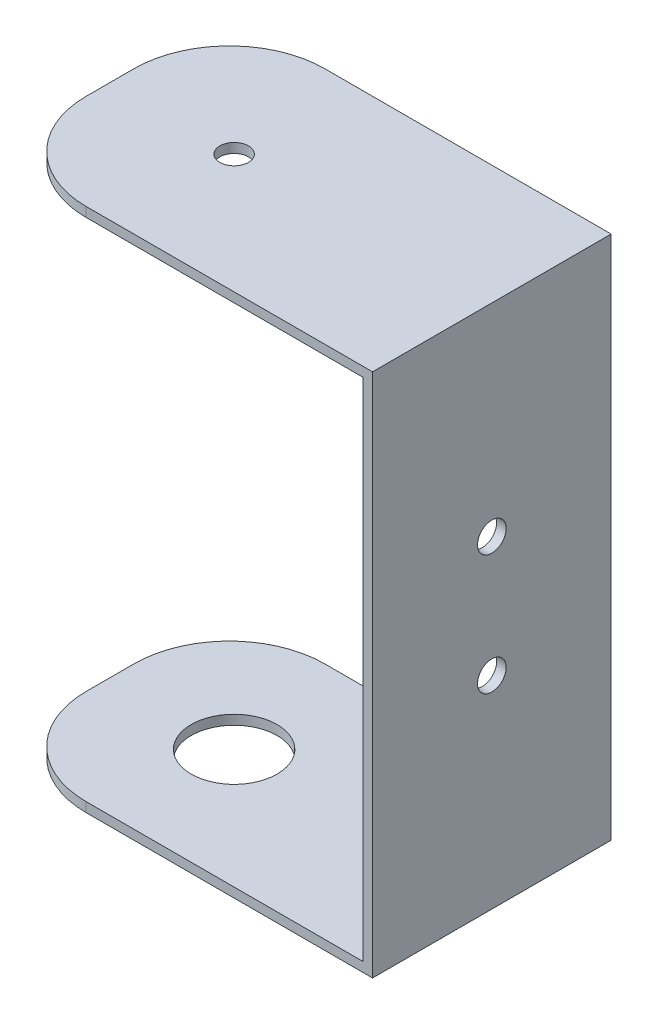
SolidWorks part; units mm, degrees
ref_plane "Alzado" through (0, 0, 0) normal (0, 0, 1) x (1, 0, 0)
ref_plane "Planta" through (0, 0, 0) normal (0, 1, 0) x (1, 0, 0)
ref_plane "Vista lateral" through (0, 0, 0) normal (1, 0, 0) x (0, 0, -1)
sketch "Croquis1" plane through (0, 0, 0) normal (0, 0, 1) x (1, 0, 0)
  line L0 (0, 17.1493) -> (0, -35.8507)
  line L1 (0, -35.8507) -> (-39, -35.8507)
  line L2 (0, 17.1493) -> (-39, 17.1493)
  dimension "D1" = 39
  dimension "D2" = 39
  dimension "D3" = 53
extrude "Extruir-Lámina1" add sketch "Croquis1" along normal blind 25 thin thin type one direction wall 1
sketch "Croquis2" plane through (0, 18.1493, 0) normal (0, 1, 0) x (1, 0, 0)
  circle A0 centre (-26, -12.5) radius 1.5
extrude "Cortar-Extruir1" cut sketch "Croquis2" against normal blind 1
sketch "Croquis5" plane through (0, -36.8507, 0) normal (0, -1, 0) x (1, 0, 0)
  circle A0 centre (-26, 12.5) radius 4.5
extrude "Cortar-Extruir2" cut sketch "Croquis5" against normal blind 1
sketch "Croquis6" plane through (1, 0, 0) normal (1, 0, 0) x (0, 0, -1)
  circle A0 centre (-12.5, -15.6507) radius 1.5
  circle A1 centre (-12.5, -3.0507) radius 1.5
extrude "Cortar-Extruir3" cut sketch "Croquis6" against normal blind 1
fillet "Redondeo1" radius 10 4 edges at (-39, 17.6493, 25) (-39, 17.6493, 0) (-39, -36.3507, 0) (-39, -36.3507, 25)
